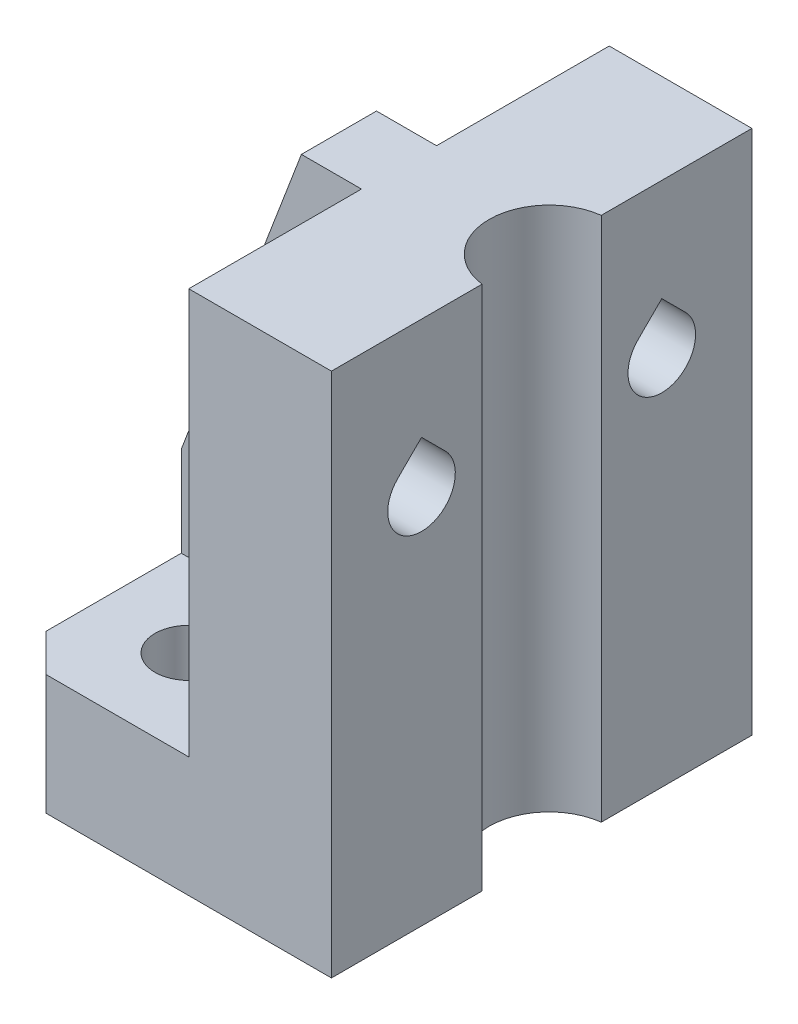
SolidWorks part; units mm, degrees
material "Printed PLA"
ref_plane "Front Plane" through (0, 0, 0) normal (0, 0, 1) x (1, 0, 0)
ref_plane "Top Plane" through (0, 0, 0) normal (0, 1, 0) x (1, 0, 0)
ref_plane "Right Plane" through (0, 0, 0) normal (1, 0, 0) x (0, 0, -1)
sketch "Sketch1" plane through (0, 0, 0) normal (0, 0, 1) x (1, 0, 0)
  line L1 (0, 0) -> (-22, 0)
  line L2 (0, 0) -> (0, 35)
  line L3 (0, 35) -> (-10, 35)
  line L4 (-22, 0) -> (-22, 8)
  line L7 (-22, 8) -> (-10, 8)
  line L8 (-10, 35) -> (-10, 8)
  dimension "D1" = 8
  dimension "D2" = 10
  dimension "D3" = 12
  dimension "D4" = 35
extrude "Boss-Extrude1" add sketch "Sketch1" along normal mid plane 28
sketch "Sketch2" plane through (0, 35, 0) normal (0, 1, 0) x (1, 0, 0)
  circle A0 centre (0, 0) radius 4
  dimension "D1" = 8
extrude "Cut-Extrude1" cut sketch "Sketch2" against normal through all
sketch "Sketch3" plane through (0, 35, 0) normal (0, 1, 0) x (1, 0, 0)
  line L0 (0, -14) -> (-10, -14) construction
  line L1 (0, 14) -> (-0.5, 14)
  line L2 (0, 14) -> (0, -14)
  line L3 (0, -14) -> (-0.5, -14)
  line L4 (-0.5, 14) -> (-0.5, -14)
  dimension "D1" = 0.5
extrude "Cut-Extrude2" cut sketch "Sketch3" against normal through all
sketch "Sketch4" plane through (0, 8, 0) normal (0, 1, 0) x (1, 0, 0)
  line L0 (-16, -8) -> (-16, 8) construction
  line L1 (-16, 0) -> (0, 0) construction
  line L2 (-16, 8) -> (-16, 14) construction
  line L3 (-10, 14) -> (-22, 14) construction
  circle A0 centre (-16, 8) radius 2.25
  circle A1 centre (-16, -8) radius 2.25
  dimension "D2" = 4.5
  dimension "D1" = 16
extrude "Cut-Extrude3" cut sketch "Sketch4" against normal through all
sketch "Sketch5" plane through (-10, 0, 0) normal (-1, 0, 0) x (0, 0, 1)
  line L0 (6.409, 26.591) -> (8, 28.182)
  line L1 (8, 28.182) -> (9.591, 26.591)
  line L2 (-9.591, 26.591) -> (-8, 28.182)
  line L3 (-8, 28.182) -> (-6.409, 26.591)
  line L4 (-8, 28.182) -> (-8, 25) construction
  line L5 (-8, 25) -> (8, 25) construction
  line L6 (8, 25) -> (8, 28.182) construction
  line L7 (0, 25) -> (0, 0) construction
  line L8 (14, 35) -> (-14, 35) construction
  arc A0 (-9.591, 26.591) -> (-6.409, 26.591) centre (-8, 25) ccw
  arc A1 (6.409, 26.591) -> (9.591, 26.591) centre (8, 25) ccw
  dimension "D1" = 4.5
  dimension "D2" = 16
  dimension "D3" = 10
extrude "Cut-Extrude4" cut sketch "Sketch5" against normal through all
chamfer "Chamfer1" distance 2.5 angle 45 2 edges at (-22, 4, -14) (-22, 4, 14)
sketch "Sketch6" plane through (0, 0, 0) normal (0, 0, 1) x (1, 0, 0)
  line L0 (-22, 8) -> (-22, 14)
  line L1 (-22, 14) -> (-14, 35)
  line L2 (-14, 35) -> (-10, 35)
  line L3 (-10, 35) -> (-10, 8)
  line L4 (-10, 8) -> (-22, 8)
  dimension "D1" = 6
  dimension "D2" = 4
extrude "Boss-Extrude2" add sketch "Sketch6" along normal mid plane 5
